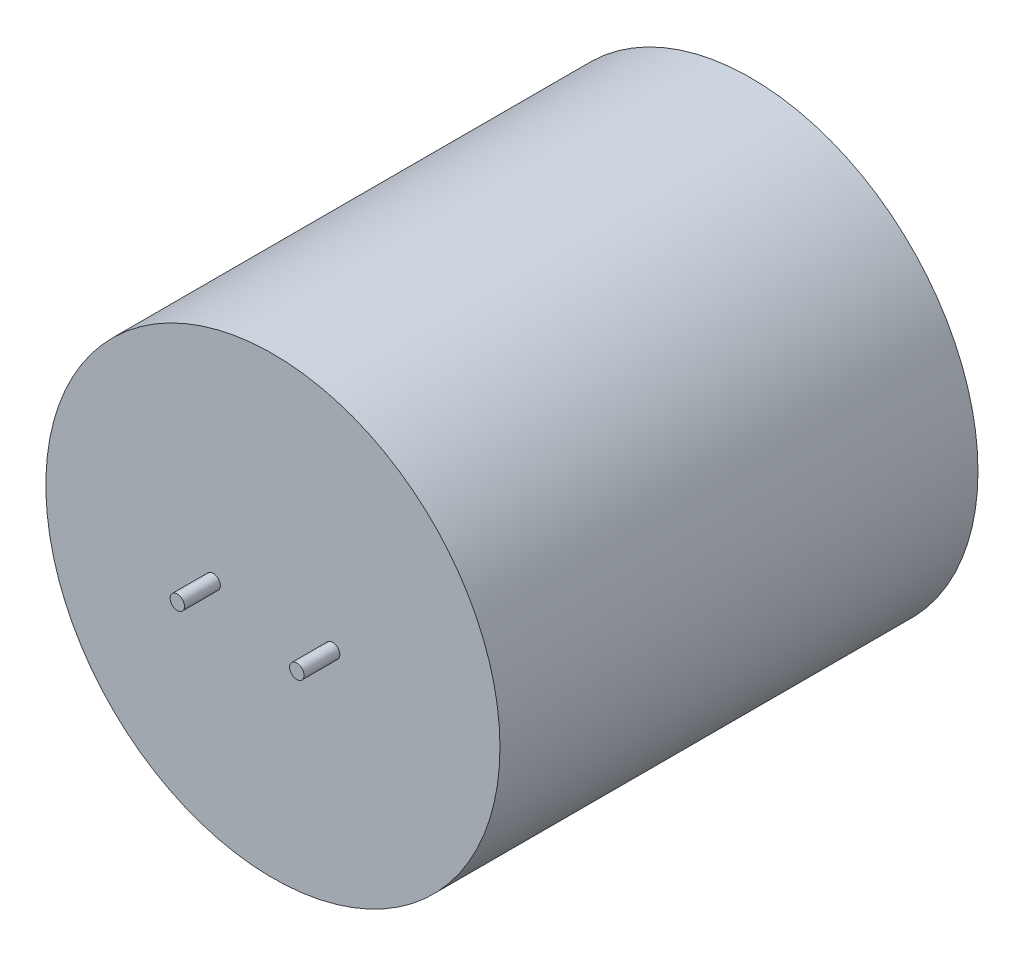
SolidWorks part; units mm, degrees
ref_plane "Спереди" through (0, 0, 0) normal (0, 0, 1) x (1, 0, 0)
ref_plane "Сверху" through (0, 0, 0) normal (0, 1, 0) x (1, 0, 0)
ref_plane "Справа" through (0, 0, 0) normal (1, 0, 0) x (0, 0, -1)
sketch "Эскиз1" plane through (0, 0, 0) normal (0, 0, 1) x (1, 0, 0)
  circle A0 centre (0, 0) radius 19
  dimension "D1" = 38
extrude "Вытянуть1" add sketch "Эскиз1" along normal blind 40
sketch "Эскиз2" plane through (0, 0, 40) normal (0, 0, 1) x (1, 0, 0)
  line L0 (0, 17.1388) -> (0, -17.9559) construction
  line L1 (-17.3108, 0) -> (19.9343, 0) construction
  circle A0 centre (-5, 0) radius 0.6
  circle A1 centre (5, 0) radius 0.6
  dimension "D1" = 1.2
  dimension "D2" = 10
extrude "Вытянуть2" add sketch "Эскиз2" along normal blind 3
